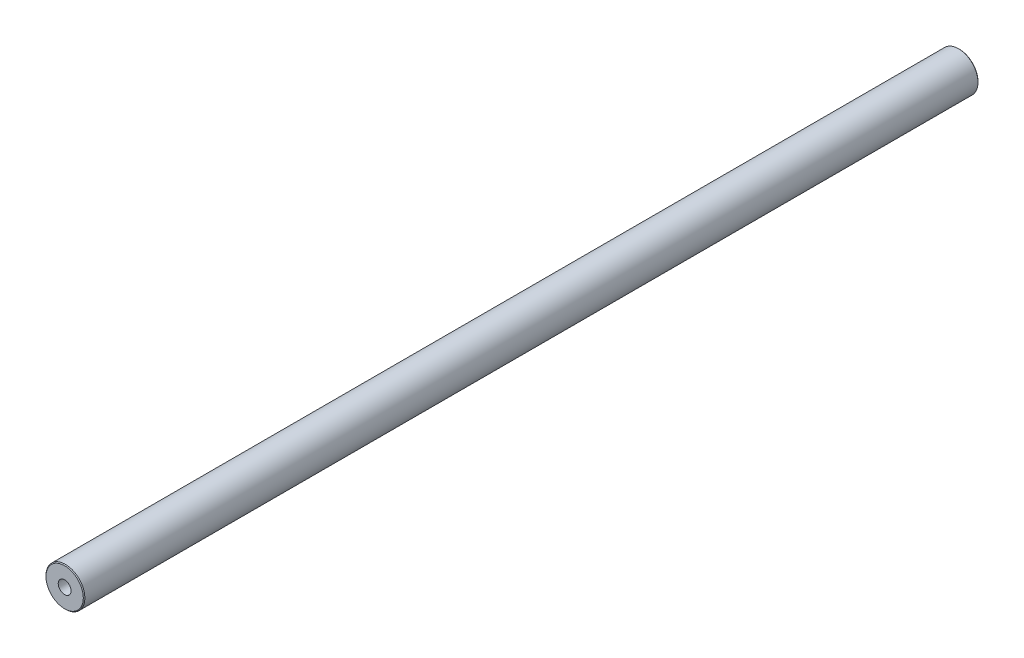
SolidWorks part; units mm, degrees
material "A2017"
ref_plane "正面" through (0, 0, 0) normal (0, 0, 1) x (1, 0, 0)
ref_plane "平面" through (0, 0, 0) normal (0, 1, 0) x (1, 0, 0)
ref_plane "右側面" through (0, 0, 0) normal (1, 0, 0) x (0, 0, -1)
sketch "ｽｹｯﾁ1" plane through (0, 0, 0) normal (0, 0, 1) x (1, 0, 0)
  circle A0 centre (0, 0) radius 5
  dimension "D1" = 10
extrude "ﾎﾞｽ - 押し出し1" add sketch "ｽｹｯﾁ1" along normal mid plane 230
hole_wizard "M4x0.7 ねじ穴1" positions "ｽｹｯﾁ4" profile "ｽｹｯﾁ3" tap size "M4x0.7" standard "Jis"
sketch "ｽｹｯﾁ4" plane through (0, 0, 115) normal (0, 0, 1) x (1, 0, 0)
  point P0 (0, 0)
sketch "ｽｹｯﾁ3" plane through (0, 0, 115) normal (1, 0, 0) x (0, -1, 0)
  line L0 (0, 0) -> (0, 12.4914)
  line L1 (0, 12.4914) -> (1.65, 11.5)
  line L2 (1.65, 11.5) -> (1.65, 0)
  line L5 (1.65, 0) -> (0, 0)
  line L10 (0, 12.4914) -> (-1.65, 11.5) construction
  line L11 (0, -6.35) -> (0, 107.95) construction
  dimension "ねじ下穴ﾄﾞﾘﾙ直径" = 3.3
  dimension "ねじ下穴ﾄﾞﾘﾙの深さ" = 11.5
  dimension "ﾄﾞﾘﾙ角度" = 118
cosmetic thread "穴のねじ山1"
mirror "ﾐﾗｰ1" about plane through (0, 0, 0) normal (0, 0, 1) of "M4x0.7 ねじ穴1"
chamfer "面取り1" distance 0.2 angle 45 2 edges at (5, 0, -115) (5, 0, 115)
